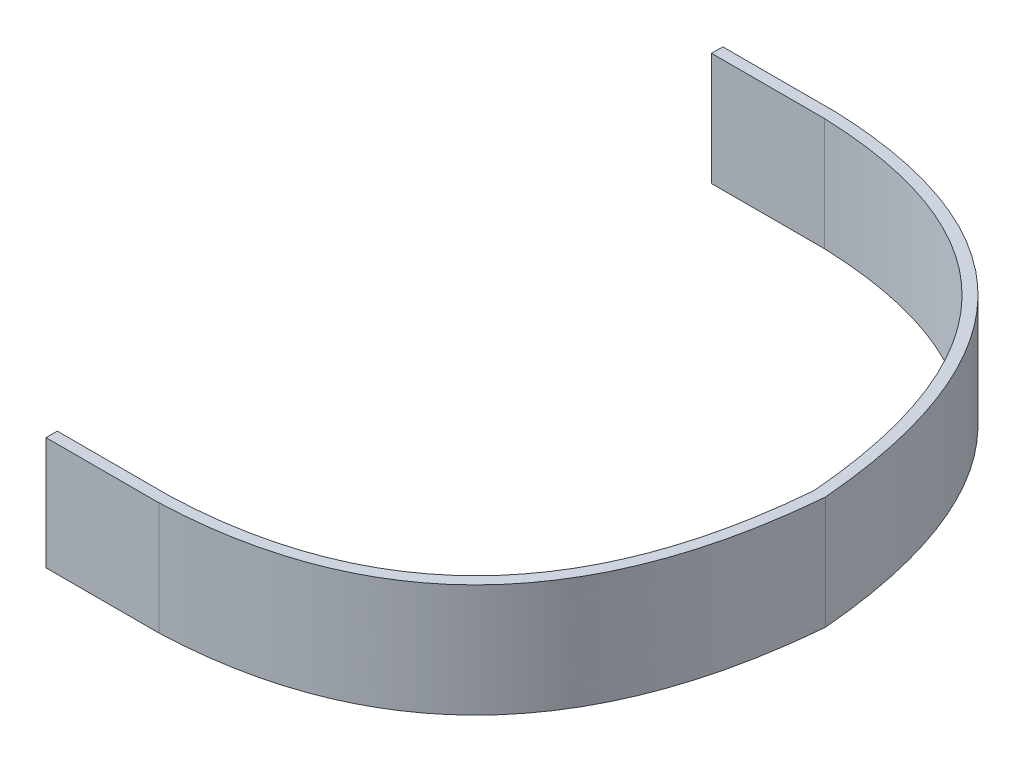
SolidWorks part; units mm, degrees
ref_plane "Front Plane" through (0, 0, 0) normal (0, 0, 1) x (1, 0, 0)
ref_plane "Top Plane" through (0, 0, 0) normal (0, 1, 0) x (1, 0, 0)
ref_plane "Right Plane" through (0, 0, 0) normal (1, 0, 0) x (0, 0, -1)
sketch "Sketch1" plane through (0, 0, 0) normal (0, 1, 0) x (1, 0, 0)
  line L0 (384.729, -422.663) -> (561.673, -422.663) construction
  line L1 (0, 90) -> (0, -90)
  point P4 (0, 0)
  point P6 (0, 0)
  dimension "D1" = 180
sketch "Sketch2" plane through (0, 0, 0) normal (0, 1, 0) x (1, 0, 0)
  line L0 (0, 90) -> (-30, 90)
  line L1 (-30, 90) -> (-30, 87)
  line L2 (-30, 87) -> (0, 87)
  line L3 (0, 90) -> (0, -90) construction
  line L4 (0, 0) -> (84.316, 0) construction
  line L5 (52.4206, 74.1395) -> (0, 0) construction
  line L6 (-30, -87) -> (0, -87)
  line L7 (-30, -90) -> (-30, -87)
  line L8 (0, -90) -> (-30, -90)
  spline S0 degree 2 poles (0, 90) (79.9739, 87.051) (87.316, 0) knots 0 0 0 1 1 1
  spline S1 degree 2 poles (0, 87) (77.3468, 84.2114) (84.316, 0) knots 0 0 0 1 1 1
  spline S2 degree 2 poles (0, -87) (77.3468, -84.2114) (84.316, 0) knots 0 0 0 1 1 1
  spline S3 degree 2 poles (0, -90) (79.9739, -87.051) (87.316, 0) knots 0 0 0 1 1 1
  point P9 (0, 0)
  point P12 (87.316, 0)
  point P15 (46.012, 81.49)
  point P17 (45.4749, 79.147)
  point P18 (1.7944, 0)
  point P19 (52.4206, 74.1395)
  dimension "D1" = 3
  dimension "D2" = 3
  dimension "D3" = 30
  dimension "D4" = 3
extrude "Boss-Extrude1" add sketch "Sketch2" along normal blind 30
